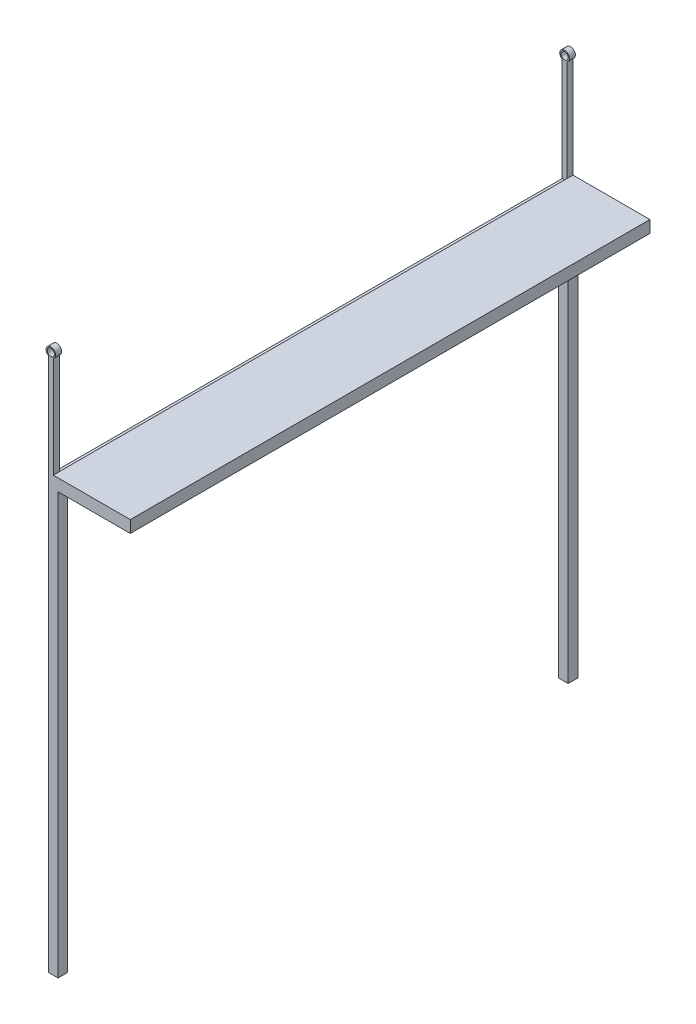
SolidWorks part; units mm, degrees
ref_plane "Front Plane" through (0, 0, 0) normal (0, 0, 1) x (1, 0, 0)
ref_plane "Top Plane" through (0, 0, 0) normal (0, 1, 0) x (1, 0, 0)
ref_plane "Right Plane" through (0, 0, 0) normal (1, 0, 0) x (0, 0, -1)
sketch "Sketch1" plane through (0, 0, 0) normal (0, 1, 0) x (1, 0, 0)
  line L1 (-25.4, -1371.6) -> (25.4, -1371.6)
  line L2 (-25.4, -1371.6) -> (-25.4, 1371.6)
  line L3 (-25.4, 1371.6) -> (25.4, 1371.6)
  line L4 (25.4, -1371.6) -> (25.4, 1371.6)
  line L5 (-25.4, -1371.6) -> (25.4, 1371.6) construction
  line L6 (-25.4, 1371.6) -> (25.4, -1371.6) construction
  point P0 (0, 0)
  dimension "D1" = 50.8
  dimension "D2" = 2743.2
extrude "Boss-Extrude1" add sketch "Sketch1" along normal blind 50.8
ref_plane "Plane1" through (0, 0, 1371.6) normal (0, 0, 1) x (1, 0, 0)
sketch "Sketch2" plane through (0, 0, 1371.6) normal (0, 0, 1) x (1, 0, 0)
  line L0 (25.4, 50.8) -> (25.4, 596.9)
  line L1 (25.4, 50.8) -> (0, 50.8)
  line L2 (-25.4, 50.8) -> (25.4, 50.8) construction
  line L3 (0, 596.9) -> (0, 50.8)
  line L5 (-25.4, 50.8) -> (0, 50.8)
  circle A0 centre (12.7, 618.897) radius 25.4
  circle A1 centre (12.7, 618.897) radius 19.05
  dimension "D2" = 50.8
  dimension "D3" = 38.1
  dimension "D1" = 546.1
  dimension "D4" = 25.4
  dimension "D5" = 25.4
extrude "Boss-Extrude2" add sketch "Sketch2" against normal blind 31.75
mirror "Mirror1" about plane through (0, 0, 0) normal (0, 0, 1) of "Boss-Extrude2"
sketch "Sketch3" plane through (25.4, 0, 0) normal (1, 0, 0) x (0, 0, -1)
  line L0 (1371.6, 596.9) -> (1371.6, 0) construction
  line L1 (-1371.6, 0) -> (1371.6, 0)
  line L2 (-1371.6, 0) -> (-1371.6, 50.8)
  line L3 (-1371.6, 50.8) -> (1371.6, 50.8)
  line L4 (1371.6, 0) -> (1371.6, 50.8)
extrude "Boss-Extrude3" add sketch "Sketch3" along normal blind 279.4
sketch "Sketch4" plane through (0, 50.8, 0) normal (0, 1, 0) x (1, 0, 0)
  line L5 (25.4, 1371.6) -> (304.8, 1371.6)
  line L6 (25.4, 1371.6) -> (25.4, -1371.6)
  line L7 (25.4, -1371.6) -> (304.8, -1371.6)
  line L8 (304.8, 1371.6) -> (304.8, -1371.6)
extrude "Boss-Extrude4" add sketch "Sketch4" along normal blind 12.7
sketch "Sketch9" plane through (304.8, 0, 0) normal (1, 0, 0) x (0, 0, -1)
  line L1 (-1371.6, 0) -> (1371.6, 0)
  line L2 (-1371.6, 0) -> (-1371.6, 63.5)
  line L3 (-1371.6, 63.5) -> (1371.6, 63.5)
  line L4 (1371.6, 0) -> (1371.6, 63.5)
extrude "Boss-Extrude8" add sketch "Sketch9" along normal blind 127
sketch "Sketch10" plane through (0, 0, 1371.6) normal (0, 0, 1) x (1, 0, 0)
  line L1 (0, 50.8) -> (-25.4, 50.8)
  line L2 (0, 50.8) -> (0, 0)
  line L3 (0, 0) -> (-25.4, 0)
  line L4 (-25.4, 50.8) -> (-25.4, 0)
extrude "Cut-Extrude1" cut sketch "Sketch10" against normal through all both and the other way through all
sketch "Sketch11" plane through (0, 0, 0) normal (0, -1, 0) x (1, 0, 0)
  line L1 (0, 1371.6) -> (50.8, 1371.6)
  line L2 (0, 1371.6) -> (0, 1320.8)
  line L3 (0, 1320.8) -> (50.8, 1320.8)
  line L4 (50.8, 1371.6) -> (50.8, 1320.8)
  line L5 (0, -1371.6) -> (50.8, -1371.6)
  line L6 (0, -1371.6) -> (0, -1320.8)
  line L7 (0, -1320.8) -> (50.8, -1320.8)
  line L8 (50.8, -1371.6) -> (50.8, -1320.8)
  dimension "D1" = 50.8
  dimension "D2" = 50.8
  dimension "D3" = 50.8
  dimension "D4" = 50.8
extrude "Boss-Extrude9" add sketch "Sketch11" along normal blind 2222.5
